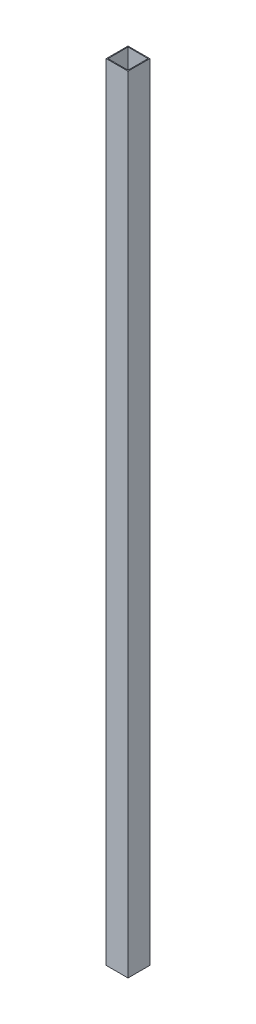
SolidWorks part; units mm, degrees
ref_plane "Front Plane" through (0, 0, 0) normal (0, 0, 1) x (1, 0, 0)
ref_plane "Top Plane" through (0, 0, 0) normal (0, 1, 0) x (1, 0, 0)
ref_plane "Right Plane" through (0, 0, 0) normal (1, 0, 0) x (0, 0, -1)
sketch "Sketch1" plane through (0, 0, 0) normal (0, 1, 0) x (1, 0, 0)
  line L0 (-23, 23) -> (23, 23)
  line L1 (-25, -25) -> (25, -25)
  line L2 (-25, -25) -> (-25, 25)
  line L3 (-25, 25) -> (25, 25)
  line L4 (25, -25) -> (25, 25)
  line L5 (-25, -25) -> (25, 25) construction
  line L6 (-25, 25) -> (25, -25) construction
  line L7 (23, -23) -> (23, 23)
  line L8 (-23, -23) -> (23, -23)
  line L9 (-23, -23) -> (-23, 23)
  point P0 (0, 0)
  dimension "D1" = 50
  dimension "D2" = 2
extrude "Boss-Extrude1" add sketch "Sketch1" along normal blind 1800
